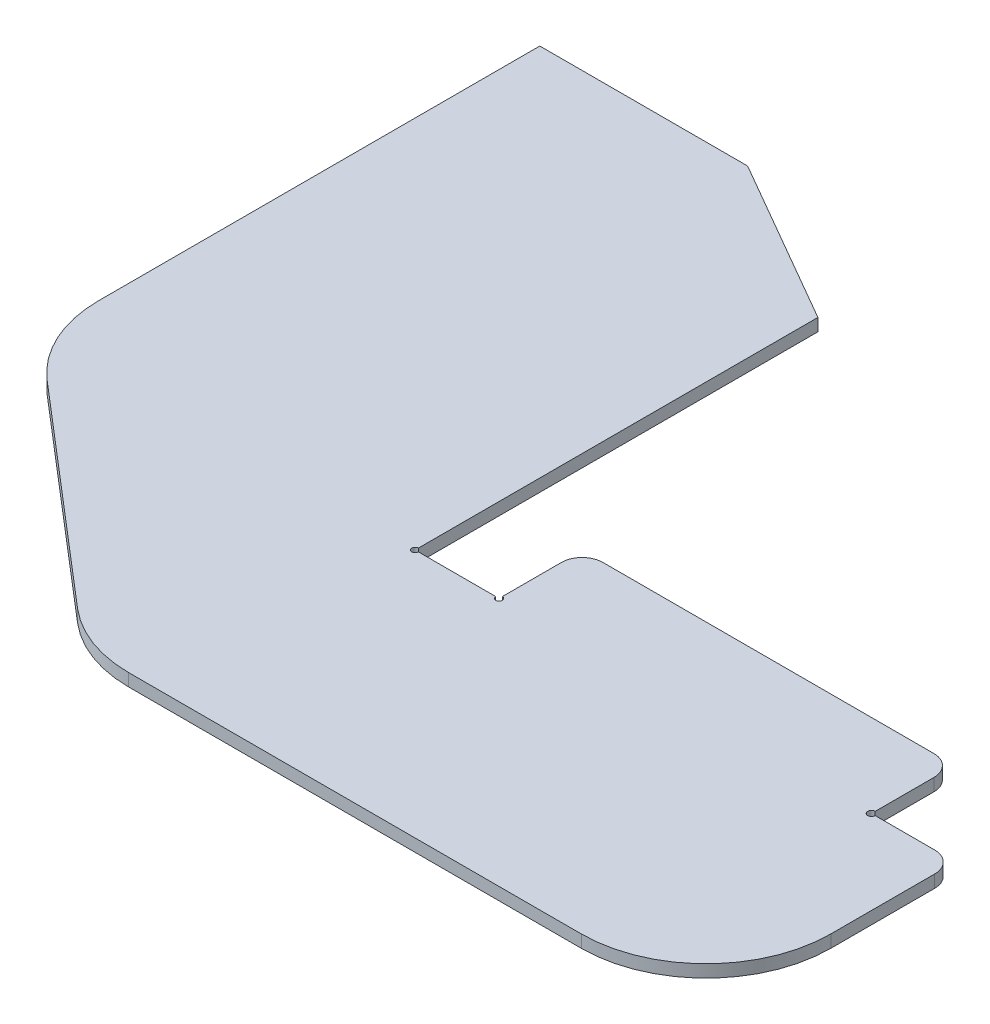
SolidWorks part; units mm, degrees
material "Thornel Mat VMA"
ref_plane "Front Plane" through (0, 0, 0) normal (0, 0, 1) x (1, 0, 0)
ref_plane "Top Plane" through (0, 0, 0) normal (0, 1, 0) x (1, 0, 0)
ref_plane "Right Plane" through (0, 0, 0) normal (1, 0, 0) x (0, 0, -1)
sketch "Sketch1" plane through (0, 0, 0) normal (0, 1, 0) x (1, 0, 0)
  line L1 (-75, -30) -> (75, -30)
  line L2 (-75, -30) -> (-75, 30)
  line L3 (-75, 30) -> (75, 30)
  line L4 (75, -30) -> (75, 30)
  line L5 (-75, -30) -> (75, 30) construction
  line L6 (-75, 30) -> (75, -30) construction
  point P0 (0, 0)
  dimension "D1" = 60
  dimension "D2" = 150
extrude "Boss-Extrude1" add sketch "Sketch1" along normal blind 3
fillet "Fillet1" radius 30 1 edges at (75, 1.5, 30)
sketch "Sketch2" plane through (0, 3, 0) normal (0, 1, 0) x (1, 0, 0)
  line L0 (75, 30) -> (-75, 30) construction
  line L1 (54.8, 30) -> (-34.8, 30)
  line L2 (54.8, 30) -> (54.8, 50)
  line L3 (54.8, 50) -> (-34.8, 50)
  line L4 (-34.8, 30) -> (-34.8, 50)
  line L5 (75, 0) -> (75, 30) construction
  line L6 (-145, 30) -> (-75, -30)
  line L7 (-55, 30) -> (-145, 30)
  line L8 (-55, 30) -> (-55, 50)
  line L9 (-55, 50) -> (-145, 50)
  line L10 (-145, 30) -> (-145, 50)
  line L11 (-75, -30) -> (-75, 30)
  line M11 (75, 30) -> (-75, 30)
  line M12 (-75, 30) -> (-75, -30)
  dimension "D1" = 89.6
  dimension "D2" = 20.2
  dimension "D3" = 20
  dimension "D4" = 20.2
  dimension "D5" = 70
extrude "Boss-Extrude2" add sketch "Sketch2" against normal up to surface (3 mm away) contours L10 L7 L8 L9 M11 | L7 L6 M12 | L4 L2 L3 M11 up to face at (10.2426, 0, 1.2426)
fillet "Fillet2" radius 30 2 edges at (-75, 1.5, 30) (-145, 1.5, -30)
sketch "Sketch3" plane through (0, 3, 0) normal (0, 1, 0) x (1, 0, 0)
  circle A0 centre (-55, 30) radius 0.8
  circle A1 centre (-34.8, 30) radius 0.8
  circle A2 centre (54.8, 30) radius 0.8994
  dimension "D1" = 1.6
extrude "Cut-Extrude1" cut sketch "Sketch3" against normal through all
fillet "Fillet3" radius 5 3 edges at (75, 1.5, -30) (54.8, 1.5, -50) (-34.8, 1.5, -50)
sketch "Sketch4" plane through (0, 0, 0) normal (0, -1, 0) x (-1, 0, 0)
  line L1 (145, 50) -> (125, 50)
  line L2 (145, 50) -> (145, 150)
  line L3 (145, 150) -> (125, 150)
  line L4 (125, 50) -> (125, 150)
  dimension "D1" = 20
  dimension "D2" = 100
extrude "Boss-Extrude3" add sketch "Sketch4" against normal up to surface (3 mm away) up to face at (-19.3965, 3, -25.0261)
sketch "Sketch5" plane through (0, 3, 0) normal (0, 1, 0) x (1, 0, 0)
  line L1 (-55, 50) -> (-125, 50)
  line L2 (-125, 50) -> (-125, 150)
  line L3 (-125, 150) -> (-95, 150)
  line L4 (-95, 150) -> (-55, 126.906)
  line L5 (-55, 126.906) -> (-55, 50)
  dimension "D1" = 120
  dimension "D2" = 30
extrude "Boss-Extrude4" add sketch "Sketch5" against normal up to surface (3 mm away) up to face at (-28.9968, 0, -36.3874)
